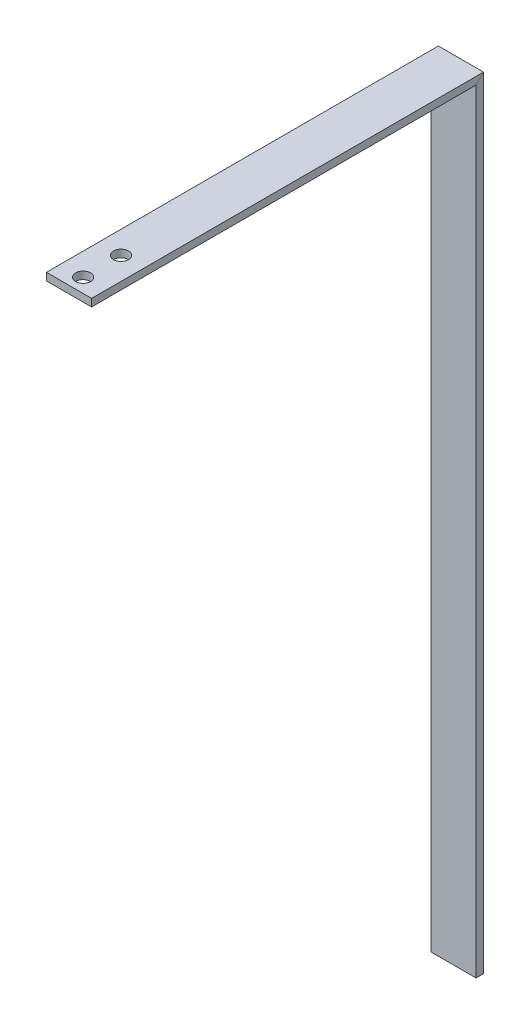
SolidWorks part; units mm, degrees
ref_plane "Alzado" through (0, 0, 0) normal (0, 0, 1) x (1, 0, 0)
ref_plane "Planta" through (0, 0, 0) normal (0, 1, 0) x (1, 0, 0)
ref_plane "Vista lateral" through (0, 0, 0) normal (1, 0, 0) x (0, 0, -1)
sketch "Croquis1" plane through (0, 0, 0) normal (0, 0, 1) x (1, 0, 0)
  line L1 (-19.05, 425.25) -> (19.05, 425.25)
  line L2 (-19.05, 425.25) -> (-19.05, -425.25)
  line L3 (-19.05, -425.25) -> (19.05, -425.25)
  line L4 (19.05, 425.25) -> (19.05, -425.25)
  line L5 (-19.05, 425.25) -> (19.05, -425.25) construction
  line L6 (-19.05, -425.25) -> (19.05, 425.25) construction
  point P0 (0, 0)
  dimension "D1" = 38.1
  dimension "D2" = 850.5
extrude "Saliente-Extruir1" add sketch "Croquis1" along normal blind 6.31
sketch "Croquis2" plane through (0, 0, 6.31) normal (0, 0, 1) x (1, 0, 0)
  line L0 (-19.05, -425.25) -> (19.05, -425.25) construction
  line L1 (-19.05, -418.94) -> (19.05, -418.94)
  line L2 (-19.05, -418.94) -> (-19.05, -425.25)
  line L3 (-19.05, -425.25) -> (19.05, -425.25)
  line L4 (19.05, -418.94) -> (19.05, -425.25)
  line L5 (-19.05, -418.94) -> (19.05, -425.25) construction
  line L6 (-19.05, -425.25) -> (19.05, -418.94) construction
  line L7 (-19.05, 425.25) -> (-19.05, -425.25) construction
  point P0 (0, -422.095)
  dimension "D1" = 6.31
extrude "Saliente-Extruir2" add sketch "Croquis2" along normal blind 70
sketch "Croquis3" plane through (0, 0, 6.31) normal (0, 0, 1) x (1, 0, 0)
  line L0 (-19.05, -425.25) -> (-19.05, -274.75) construction
  line L1 (-19.05, 425.25) -> (-19.05, -418.94) construction
  line L2 (19.05, -418.94) -> (19.05, 425.25) construction
  line L3 (-19.05, -262.4761) -> (19.05, -262.4761)
  line L4 (-19.05, -262.4761) -> (-19.05, -268.7861)
  line L5 (-19.05, -268.7861) -> (19.05, -268.7861)
  line L6 (19.05, -262.4761) -> (19.05, -268.7861)
  line L7 (-19.05, -262.4761) -> (19.05, -268.7861) construction
  line L8 (-19.05, -268.7861) -> (19.05, -262.4761) construction
  point P5 (0, -265.6311)
  dimension "D1" = 150.5
  dimension "D2" = 6.31
  dimension "D3" = 38.1
extrude "Saliente-Extruir3" add sketch "Croquis3" against normal blind 578
sketch "Croquis4" plane through (0, -262.4761, 0) normal (0, 1, 0) x (1, 0, 0)
  circle A0 centre (0, 536.9815) radius 6.9359
extrude "Cortar-Extruir1" cut sketch "Croquis4" against normal blind 7
sketch "Croquis5" plane through (0, 0, 0) normal (0, 0, -1) x (-1, 0, 0)
  line L0 (-19.05, 425.25) -> (19.05, 425.25)
  line L1 (19.05, 425.25) -> (19.05, -262.4761)
  line L2 (19.05, -262.4761) -> (-19.05, -262.4761)
  line L3 (-19.05, -262.4761) -> (-19.05, 425.25)
extrude "Cortar-Extruir2" cut sketch "Croquis5" against normal blind 10
sketch "Croquis6" plane through (0, -262.4761, 0) normal (0, 1, 0) x (1, 0, 0)
  line L0 (0, -6.31) -> (0, 196.49) construction
  line L1 (19.05, -6.31) -> (-19.05, -6.31) construction
  line L2 (19.05, 202.8) -> (-19.05, 202.8)
  line L3 (19.05, 571.69) -> (19.05, -6.31) construction
  line L4 (-19.05, 571.69) -> (-19.05, -6.31) construction
  line L5 (-19.05, 202.8) -> (-19.05, 196.49)
  line L6 (-19.05, 196.49) -> (19.05, 196.49)
  line L7 (19.05, 196.49) -> (19.05, 202.8)
  line L8 (19.05, 202.8) -> (-19.05, 196.49) construction
  line L9 (-19.05, 202.8) -> (19.05, 196.49) construction
  dimension "D1" = 202.8
  dimension "D2" = 6.31
sketch3d "Croquis3D1"
  line L0 (0, -262.4761, -199.645) -> (0, 386.8539, -199.645)
  line L1 (19.05, -262.4761, -202.8) -> (-19.05, -262.4761, -196.49) construction
  line L2 (0, 386.8539, -199.645) -> (0, 386.8539, 127.905)
  dimension "D1" = 649.33
  dimension "D2" = 327.55
sweep "Barrer1" add profiles "Croquis6" path "Croquis3D1"
sketch "Croquis8" plane through (19.05, 0, 0) normal (1, 0, 0) x (0, 0, -1)
  line L0 (196.49, -262.4761) -> (196.49, -268.7861)
  line L1 (571.69, -268.7861) -> (0, -268.7861) construction
  line L2 (196.49, -268.7861) -> (196.49, -444.3077)
  line L3 (196.49, -444.3077) -> (-90.8346, -444.3077)
  line L4 (-90.8346, -444.3077) -> (-90.8346, -262.4761)
  line L5 (-90.8346, -262.4761) -> (196.49, -262.4761)
  line L6 (202.8, -262.4761) -> (202.8, -268.7861)
  line L7 (202.8, -268.7861) -> (571.69, -268.7861)
  line L8 (571.69, -268.7861) -> (571.69, -262.4761)
  line L9 (571.69, -262.4761) -> (202.8, -262.4761)
extrude "Cortar-Extruir3" cut sketch "Croquis8" against normal blind 147
sketch "Croquis9" plane through (0, 390.0089, 0) normal (0, 1, 0) x (1, 0, 0)
  circle A0 centre (0, -84.01) radius 6.35
  circle A1 centre (0, -116.01) radius 6.35
extrude "Cortar-Extruir4" cut sketch "Croquis9" against normal blind 6.31
